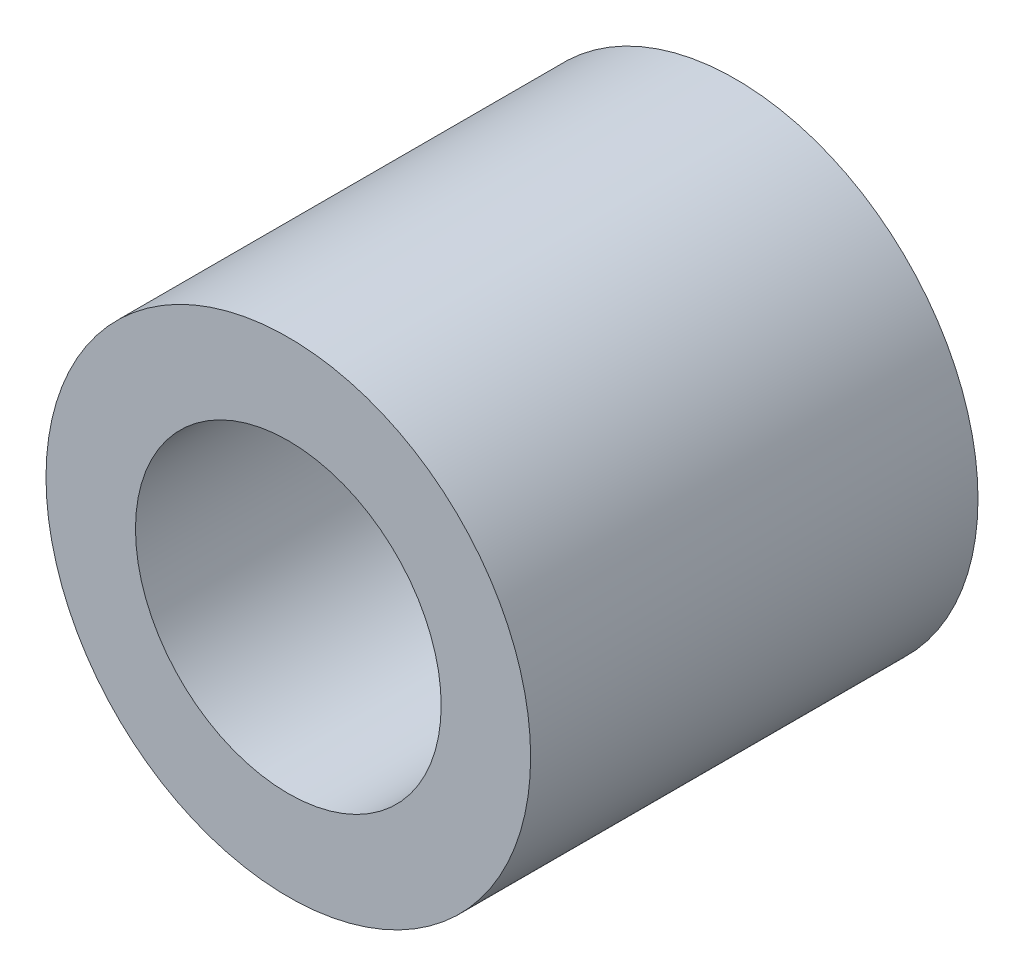
SolidWorks part; units mm, degrees
ref_plane "前视基准面" through (0, 0, 0) normal (0, 0, 1) x (1, 0, 0)
ref_plane "上视基准面" through (0, 0, 0) normal (0, 1, 0) x (1, 0, 0)
ref_plane "右视基准面" through (0, 0, 0) normal (1, 0, 0) x (0, 0, -1)
sketch "草图1" plane through (0, 0, 0) normal (0, 0, 1) x (1, 0, 0)
  circle A0 centre (0, 0) radius 1.025
  circle A1 centre (0, 0) radius 1.625
  dimension "D1" = 2.05
  dimension "D2" = 0.6
extrude "凸台-拉伸1" add sketch "草图1" along normal blind 3 from offset 0
